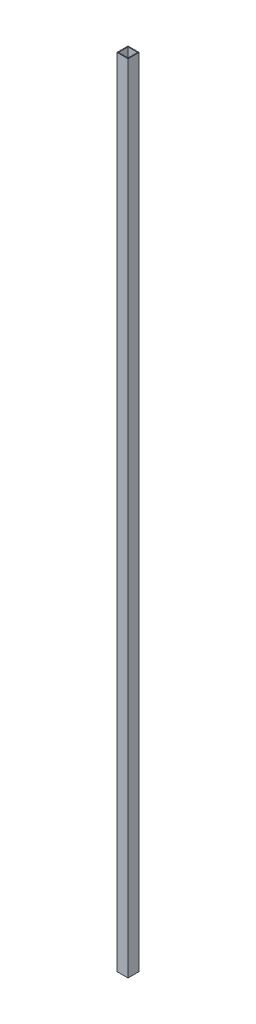
SolidWorks part; units mm, degrees
ref_plane "Front Plane" through (0, 0, 0) normal (0, 0, 1) x (1, 0, 0)
ref_plane "Top Plane" through (0, 0, 0) normal (0, 1, 0) x (1, 0, 0)
ref_plane "Right Plane" through (0, 0, 0) normal (1, 0, 0) x (0, 0, -1)
sketch "Sketch1" plane through (0, 0, 0) normal (0, 1, 0) x (1, 0, 0)
  line L1 (-12.7, -12.7) -> (12.7, -12.7)
  line L2 (-12.7, -12.7) -> (-12.7, 12.7)
  line L3 (-12.7, 12.7) -> (12.7, 12.7)
  line L4 (12.7, -12.7) -> (12.7, 12.7)
  line L5 (-12.7, -12.7) -> (12.7, 12.7) construction
  line L6 (-12.7, 12.7) -> (12.7, -12.7) construction
  line L7 (-11.1125, -11.1125) -> (11.1125, -11.1125)
  line L8 (-11.1125, -11.1125) -> (-11.1125, 11.1125)
  line L9 (-11.1125, 11.1125) -> (11.1125, 11.1125)
  line L10 (11.1125, -11.1125) -> (11.1125, 11.1125)
  line L11 (-11.1125, -11.1125) -> (11.1125, 11.1125) construction
  line L12 (-11.1125, 11.1125) -> (11.1125, -11.1125) construction
  point P0 (0, 0)
  point P6 (0, 0)
  dimension "D1" = 25.4
  dimension "D2" = 25.4
  dimension "D3" = 1.5875
  dimension "D4" = 1.5875
extrude "Boss-Extrude1" add sketch "Sketch1" along normal blind 1828.8
